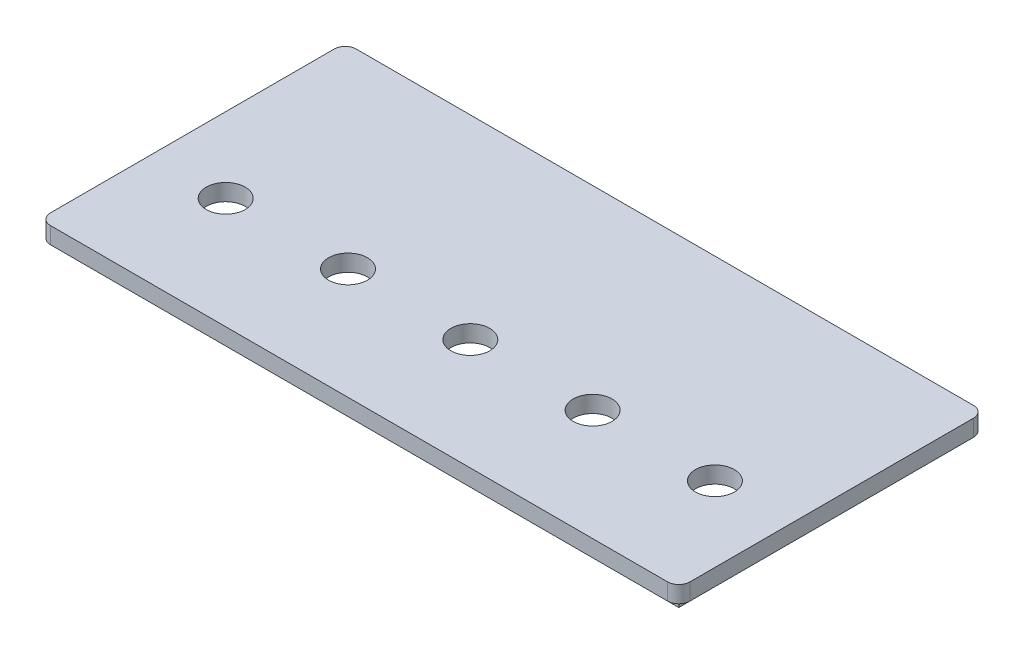
SolidWorks part; units mm, degrees
ref_plane "前视基准面" through (0, 0, 0) normal (0, 0, 1) x (1, 0, 0)
ref_plane "上视基准面" through (0, 0, 0) normal (0, 1, 0) x (1, 0, 0)
ref_plane "右视基准面" through (0, 0, 0) normal (1, 0, 0) x (0, 0, -1)
sketch "草图1" plane through (0, 0, 0) normal (0, 1, 0) x (1, 0, 0)
  line L1 (-57.5, -27.5) -> (57.5, -27.5)
  line L2 (-57.5, -27.5) -> (-57.5, 27.5)
  line L3 (-57.5, 27.5) -> (57.5, 27.5)
  line L4 (57.5, -27.5) -> (57.5, 27.5)
  line L5 (-57.5, -27.5) -> (57.5, 27.5) construction
  line L6 (-57.5, 27.5) -> (57.5, -27.5) construction
  point P0 (0, 0)
  dimension "D1" = 55
  dimension "D2" = 115
extrude "凸台-拉伸1" add sketch "草图1" along normal blind 3
sketch "草图2" plane through (0, 3, 0) normal (0, 1, 0) x (1, 0, 0)
  line L0 (-57.5, -7.5) -> (57.5, -7.5) construction
  line L1 (-57.5, 27.5) -> (-57.5, -27.5) construction
  line L2 (57.5, -27.5) -> (57.5, 27.5) construction
  line L3 (57.5, 27.5) -> (-57.5, 27.5) construction
  circle A0 centre (-44, -7.5) radius 3.5
  circle A1 centre (-22, -7.5) radius 3.5
  circle A2 centre (0, -7.5) radius 3.5
  circle A3 centre (22, -7.5) radius 3.5
  circle A4 centre (44, -7.5) radius 3.5
  point P18 (0, 0)
  point P19 (0, 0)
  dimension "D2" = 7
  dimension "D3" = 7
  dimension "D4" = 7
  dimension "D5" = 7
  dimension "7" = 7
  dimension "D1" = 35
  dimension "D7" = 22
  dimension "D8" = 22
  dimension "D9" = 22
  dimension "D10" = 22
  dimension "D11" = 57.5
extrude "切除-拉伸1" cut sketch "草图2" against normal blind 3
sketch "草图4" plane through (0, 0, 0) normal (0, -1, 0) x (1, 0, 0)
  line L0 (57.5, -27.5) -> (-57.5, -27.5) construction
  line L1 (-55.5, 25.5) -> (55.5, 25.5)
  line L2 (-55.5, 25.5) -> (-55.5, -25.5)
  line L3 (-55.5, -25.5) -> (55.5, -25.5)
  line L4 (55.5, 25.5) -> (55.5, -25.5)
  line L5 (-55.5, 25.5) -> (55.5, -25.5) construction
  line L6 (-55.5, -25.5) -> (55.5, 25.5) construction
  line L7 (57.5, 27.5) -> (57.5, -27.5) construction
  line L9 (53.5, 23.5) -> (-53.5, 23.5)
  line L10 (53.5, 23.5) -> (53.5, -23.5)
  line L11 (53.5, -23.5) -> (-53.5, -23.5)
  line L12 (-53.5, 23.5) -> (-53.5, -23.5)
  line L13 (53.5, 23.5) -> (-53.5, -23.5) construction
  line L14 (53.5, -23.5) -> (-53.5, 23.5) construction
  point P0 (0, 0)
  point P10 (0, 0)
  dimension "D1" = 2
  dimension "D2" = 2
  dimension "D3" = 2
  dimension "D4" = 2
extrude "凸台-拉伸2" add sketch "草图4" along normal blind 2
fillet "圆角1" radius 2 4 edges at (57.5, 1.5, -27.5) (-57.5, 1.5, 27.5) (-57.5, 1.5, -27.5) (57.5, 1.5, 27.5)
